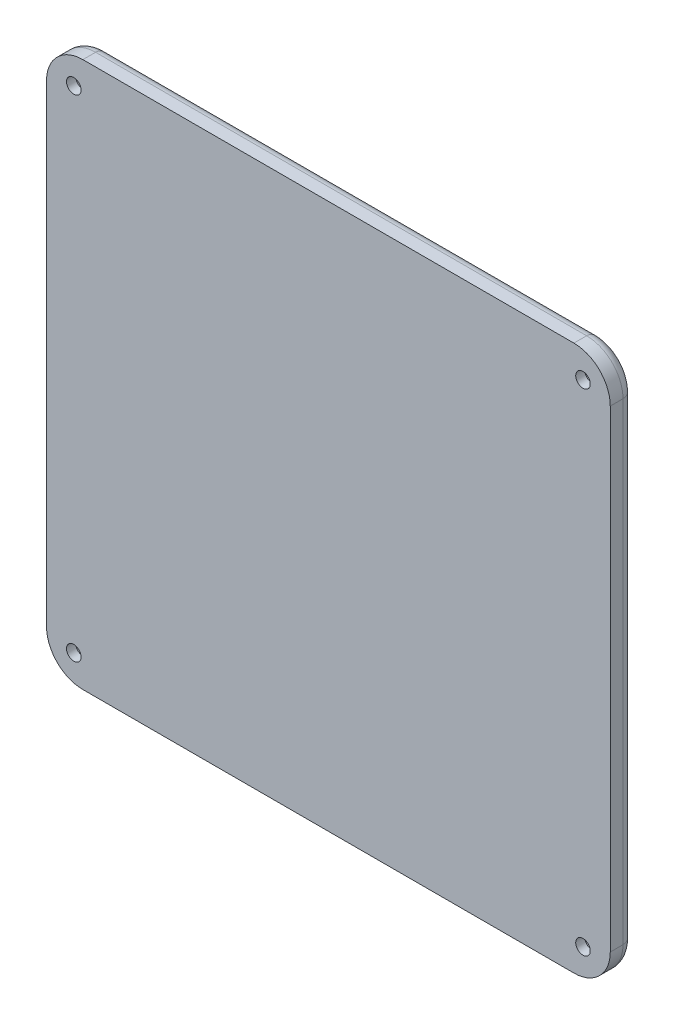
SolidWorks part; units mm, degrees
ref_plane "Front" through (0, 0, 0) normal (0, 0, 1) x (1, 0, 0)
ref_plane "Top" through (0, 0, 0) normal (0, 1, 0) x (1, 0, 0)
ref_plane "Right" through (0, 0, 0) normal (1, 0, 0) x (0, 0, -1)
sketch "Sketch1" plane through (0, 0, 0) normal (0, 0, 1) x (1, 0, 0)
  line L8 (-315, -75) -> (-180, -75)
  line L9 (-170, -65) -> (-170, 65)
  line L10 (-180, 75) -> (-315, 75)
  line L11 (-325, 65) -> (-325, -65)
  arc A8 (-180, -75) -> (-170, -65) centre (-180, -65) ccw
  arc A9 (-170, 65) -> (-180, 75) centre (-180, 65) ccw
  arc A10 (-315, 75) -> (-325, 65) centre (-315, 65) ccw
  arc A11 (-325, -65) -> (-315, -75) centre (-315, -65) ccw
  circle A12 centre (-317.5, -67.5) radius 1.25
  circle A13 centre (-177.5, -67.5) radius 1.25
  circle A14 centre (-177.5, 67.5) radius 1.25
  circle A15 centre (-317.5, 67.5) radius 1.25
extrude "Boss-Extrude1" add sketch "Sketch1" along normal blind 6.5
sketch "Sketch2" plane through (0, 0, 0) normal (0, 0, -1) x (-1, 0, 0)
  circle A0 centre (177.5, 67.5) radius 2
  circle A1 centre (317.5, 67.5) radius 2
  circle A2 centre (317.5, -67.5) radius 2
  circle A3 centre (177.5, -67.5) radius 2
  dimension "D1" = 4
  dimension "D2" = 4
  dimension "D3" = 4
  dimension "D4" = 4
extrude "Cut-Extrude1" cut sketch "Sketch2" against normal through all
fillet "Fillet1" radius 3 8 edges at (-322.0711, -72.0711, 0) (-325, 0, 0) (-322.0711, 72.0711, 0) (-247.5, 75, 0) (-172.9289, 72.0711, 0) (-170, 0, 0) (-172.9289, -72.0711, 0) (-247.5, -75, 0)
sketch "Sketch3" plane through (0, 0, 0) normal (0, 0, -1) x (-1, 0, 0)
  circle A0 centre (177.5, 67.5) radius 4
  circle A1 centre (317.5, 67.5) radius 4
  circle A2 centre (177.5, -67.5) radius 4
  circle A3 centre (317.5, -67.5) radius 4
  dimension "D1" = 8
  dimension "D2" = 8
  dimension "D3" = 8
  dimension "D4" = 8
extrude "Cut-Extrude2" cut sketch "Sketch3" against normal blind 4
